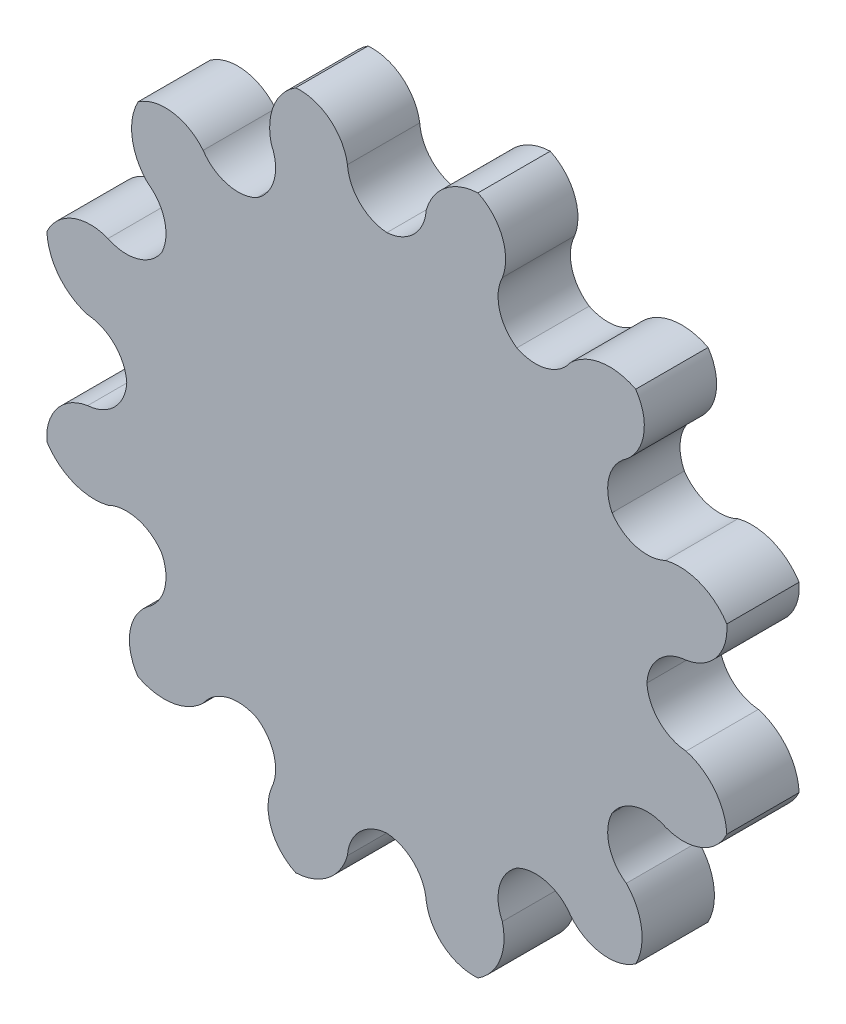
SolidWorks part; units mm, degrees
ref_plane "Front Plane" through (0, 0, 0) normal (0, 0, 1) x (1, 0, 0)
ref_plane "Top Plane" through (0, 0, 0) normal (0, 1, 0) x (1, 0, 0)
ref_plane "Right Plane" through (0, 0, 0) normal (1, 0, 0) x (0, 0, -1)
sketch "Sketch4" plane through (0, 0, 0) normal (0, 0, 1) x (1, 0, 0)
  line L0 (0, 0) -> (0, 58.4603) construction
  line L1 (0, 58.4603) -> (0, 0) construction
  line L2 (0, 0) -> (31.6195, 54.7667) construction
  line L3 (0, 2.3767) -> (0, 0) construction
  line L4 (0, 0) -> (19.7974, 73.885) construction
  line L5 (0, 0) -> (24.7992, 59.8705) construction
  line L6 (24.7992, 59.8705) -> (0, 0) construction
  line L7 (0, 0) -> (8.6468, 65.6788) construction
  circle A0 centre (0, 0) radius 21.5738 construction
  circle A1 centre (0, 0) radius 25.0369 construction
  circle A2 centre (0, 0) radius 29.196 construction
  arc A3 (0, 21.5738) -> (3.268, 24.8227) centre (-0.2235, 25.0667) ccw
  arc A4 (3.268, 24.8227) -> (7.5565, 28.2012) centre (7.7486, 23.5462) cw
  arc A5 (7.5565, 28.2012) -> (9.5812, 23.131) centre (5.8535, 24.5818) cw
  arc A6 (9.5812, 23.131) -> (10.7869, 18.6835) centre (12.7269, 21.5966) ccw
  arc A7 (10.7869, 18.6835) -> (15.2415, 19.8631) centre (12.3398, 21.8201) ccw
  arc A8 (15.2415, 19.8631) -> (20.6447, 20.6447) centre (18.4836, 16.5173) cw
  arc A9 (20.6447, 20.6447) -> (19.8631, 15.2415) centre (17.3602, 18.3617) cw
  arc A10 (19.8631, 15.2415) -> (18.6835, 10.7869) centre (21.8201, 12.3398) ccw
  arc A11 (18.6835, 10.7869) -> (23.131, 9.5812) centre (21.5966, 12.7269) ccw
  arc A12 (23.131, 9.5812) -> (28.2012, 7.5565) centre (24.266, 5.0626) cw
  arc A13 (28.2012, 7.5565) -> (24.8227, 3.268) centre (24.2152, 7.2216) cw
  arc A14 (24.8227, 3.268) -> (21.5738, 0) centre (25.0667, -0.2235) ccw
  arc A15 (21.5738, 0) -> (24.8227, -3.268) centre (25.0667, 0.2235) ccw
  arc A16 (24.8227, -3.268) -> (28.2012, -7.5565) centre (23.5462, -7.7486) cw
  arc A17 (28.2012, -7.5565) -> (23.131, -9.5812) centre (24.5818, -5.8535) cw
  arc A18 (23.131, -9.5812) -> (18.6835, -10.7869) centre (21.5966, -12.7269) ccw
  arc A19 (18.6835, -10.7869) -> (19.8631, -15.2415) centre (21.8201, -12.3398) ccw
  arc A20 (19.8631, -15.2415) -> (20.6447, -20.6447) centre (16.5173, -18.4836) cw
  arc A21 (20.6447, -20.6447) -> (15.2415, -19.8631) centre (18.3617, -17.3602) cw
  arc A22 (15.2415, -19.8631) -> (10.7869, -18.6835) centre (12.3398, -21.8201) ccw
  arc A23 (10.7869, -18.6835) -> (9.5812, -23.131) centre (12.7269, -21.5966) ccw
  arc A24 (9.5812, -23.131) -> (7.5565, -28.2012) centre (5.0626, -24.266) cw
  arc A25 (7.5565, -28.2012) -> (3.268, -24.8227) centre (7.2216, -24.2152) cw
  arc A26 (3.268, -24.8227) -> (0, -21.5738) centre (-0.2235, -25.0667) ccw
  arc A27 (0, -21.5738) -> (-3.268, -24.8227) centre (0.2235, -25.0667) ccw
  arc A28 (-3.268, -24.8227) -> (-7.5565, -28.2012) centre (-7.7486, -23.5462) cw
  arc A29 (-7.5565, -28.2012) -> (-9.5812, -23.131) centre (-5.8535, -24.5818) cw
  arc A30 (-9.5812, -23.131) -> (-10.7869, -18.6835) centre (-12.7269, -21.5966) ccw
  arc A31 (-10.7869, -18.6835) -> (-15.2415, -19.8631) centre (-12.3398, -21.8201) ccw
  arc A32 (-15.2415, -19.8631) -> (-20.6447, -20.6447) centre (-18.4836, -16.5173) cw
  arc A33 (-20.6447, -20.6447) -> (-19.8631, -15.2415) centre (-17.3602, -18.3617) cw
  arc A34 (-19.8631, -15.2415) -> (-18.6835, -10.7869) centre (-21.8201, -12.3398) ccw
  arc A35 (-18.6835, -10.7869) -> (-23.131, -9.5812) centre (-21.5966, -12.7269) ccw
  arc A36 (-23.131, -9.5812) -> (-28.2012, -7.5565) centre (-24.266, -5.0626) cw
  arc A37 (-28.2012, -7.5565) -> (-24.8227, -3.268) centre (-24.2152, -7.2216) cw
  arc A38 (-24.8227, -3.268) -> (-21.5738, 0) centre (-25.0667, 0.2235) ccw
  arc A39 (-21.5738, 0) -> (-24.8227, 3.268) centre (-25.0667, -0.2235) ccw
  arc A40 (-24.8227, 3.268) -> (-28.2012, 7.5565) centre (-23.5462, 7.7486) cw
  arc A41 (-28.2012, 7.5565) -> (-23.131, 9.5812) centre (-24.5818, 5.8535) cw
  arc A42 (-23.131, 9.5812) -> (-18.6835, 10.7869) centre (-21.5966, 12.7269) ccw
  arc A43 (-18.6835, 10.7869) -> (-19.8631, 15.2415) centre (-21.8201, 12.3398) ccw
  arc A44 (-19.8631, 15.2415) -> (-20.6447, 20.6447) centre (-16.5173, 18.4836) cw
  arc A45 (-20.6447, 20.6447) -> (-15.2415, 19.8631) centre (-18.3617, 17.3602) cw
  arc A46 (-15.2415, 19.8631) -> (-10.7869, 18.6835) centre (-12.3398, 21.8201) ccw
  arc A47 (-10.7869, 18.6835) -> (-9.5812, 23.131) centre (-12.7269, 21.5966) ccw
  arc A48 (-9.5812, 23.131) -> (-7.5565, 28.2012) centre (-5.0626, 24.266) cw
  arc A49 (-7.5565, 28.2012) -> (-3.268, 24.8227) centre (-7.2216, 24.2152) cw
  arc A50 (-3.268, 24.8227) -> (0, 21.5738) centre (0.2235, 25.0667) ccw
  point P122 (0, 0)
  dimension "D1" = 30
  dimension "D3" = 7.5
  dimension "D4" = 7.5
  dimension "D6" = 12
  dimension "D2" = 15
extrude "Boss-Extrude4" add sketch "Sketch4" along normal blind 6
